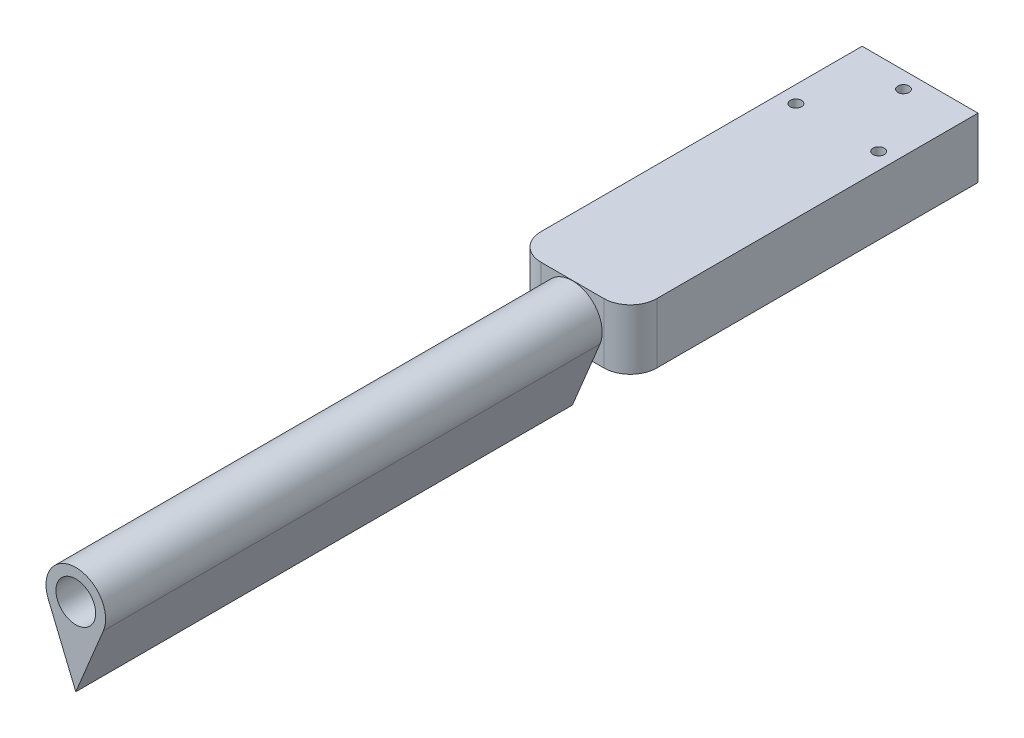
SolidWorks part; units mm, degrees
ref_plane "Ön Düzlem" through (0, 0, 0) normal (0, 0, 1) x (1, 0, 0)
ref_plane "Üst Düzlem" through (0, 0, 0) normal (0, 1, 0) x (1, 0, 0)
ref_plane "Sağ Düzlem" through (0, 0, 0) normal (1, 0, 0) x (0, 0, -1)
sketch "Çizim1" plane through (0, 0, 0) normal (0, 0, 1) x (1, 0, 0)
  line L0 (0, -23.5308) -> (8.3157, -3.4423)
  line L1 (0, -23.5308) -> (-8.3157, -3.4423)
  arc A0 (8.3157, -3.4423) -> (-8.3157, -3.4423) centre (0, 0) ccw
  circle A1 centre (0, 0) radius 6
extrude "Yükseklik-Ekstrüzyon1" add sketch "Çizim1" along normal blind 150
sketch "Çizim2" plane through (0, 0, 0) normal (0, 0, 1) x (1, 0, 0)
  line L1 (-17.5, 9.0847) -> (17.5, 9.0847)
  line L2 (-17.5, 9.0847) -> (-17.5, -9.0847)
  line L3 (-17.5, -9.0847) -> (17.5, -9.0847)
  line L4 (17.5, 9.0847) -> (17.5, -9.0847)
  line L5 (-17.5, 9.0847) -> (17.5, -9.0847) construction
  line L6 (-17.5, -9.0847) -> (17.5, 9.0847) construction
  point P0 (0, 0)
extrude "Yükseklik-Ekstrüzyon2" add sketch "Çizim2" against normal blind 105
fillet "Radyus1" radius 8 2 edges at (17.5, 0, 0) (-17.5, 0, 0)
sketch "Çizim3" plane through (0, 9.0847, 0) normal (0, 1, 0) x (1, 0, 0)
  line L0 (17.5, 105) -> (17.5, 8) construction
  line L1 (-17.5, 105) -> (17.5, 105)
  line L2 (-17.5, 105) -> (-17.5, 75)
  line L3 (-17.5, 75) -> (17.5, 75)
  line L4 (17.5, 105) -> (17.5, 75)
  line L5 (0, 105) -> (0, 100)
  line L6 (-17.5, 75) -> (-12.5, 75)
  line L7 (-17.5, 75) -> (-17.5, 80)
  line L8 (-17.5, 80) -> (-12.5, 80)
  line L9 (-12.5, 75) -> (-12.5, 80)
  line L10 (17.5, 75) -> (12.5, 75)
  line L11 (17.5, 75) -> (17.5, 80)
  line L12 (17.5, 80) -> (12.5, 80)
  line L13 (12.5, 75) -> (12.5, 80)
hole_wizard "M3 Boşluklu Delik1" positions "Çizim4" profile "Çizim5" hole size "M3" standard "ANSI Metrik" end condition through all
sketch "Çizim4" plane through (0, 9.0847, 0) normal (0, 1, 0) x (1, 0, 0)
  point P0 (-12.5, 80)
  point P3 (12.5, 80)
  point P6 (0, 100)
sketch "Çizim5" plane through (-12.5, 9.0847, -80) normal (1, 0, 0) x (0, 0, 1)
  line L0 (0, 0) -> (0, 32.6155)
  line L1 (0, 32.6155) -> (1.7, 32.6155)
  line L2 (1.7, 32.6155) -> (1.7, 0)
  line L5 (1.7, 0) -> (0, 0)
  line L11 (0, -6.35) -> (0, 107.95) construction
  dimension "Thru Hole Dia." = 3.4
  dimension "Thru Hole Depth" = 32.6155
sketch "Çizim8" plane through (0, 0, 0) normal (0, 0, 1) x (1, 0, 0)
  circle A0 centre (0, 0) radius 6
extrude "Kes-Ekstrüzyon1" cut sketch "Çizim8" against normal blind 105
sketch "Çizim9" plane through (0, -9.0847, 0) normal (0, -1, 0) x (1, 0, 0)
  circle A0 centre (0, -11.5395) radius 6.3191
extrude "Kes-Ekstrüzyon2" cut sketch "Çizim9" against normal blind 10
